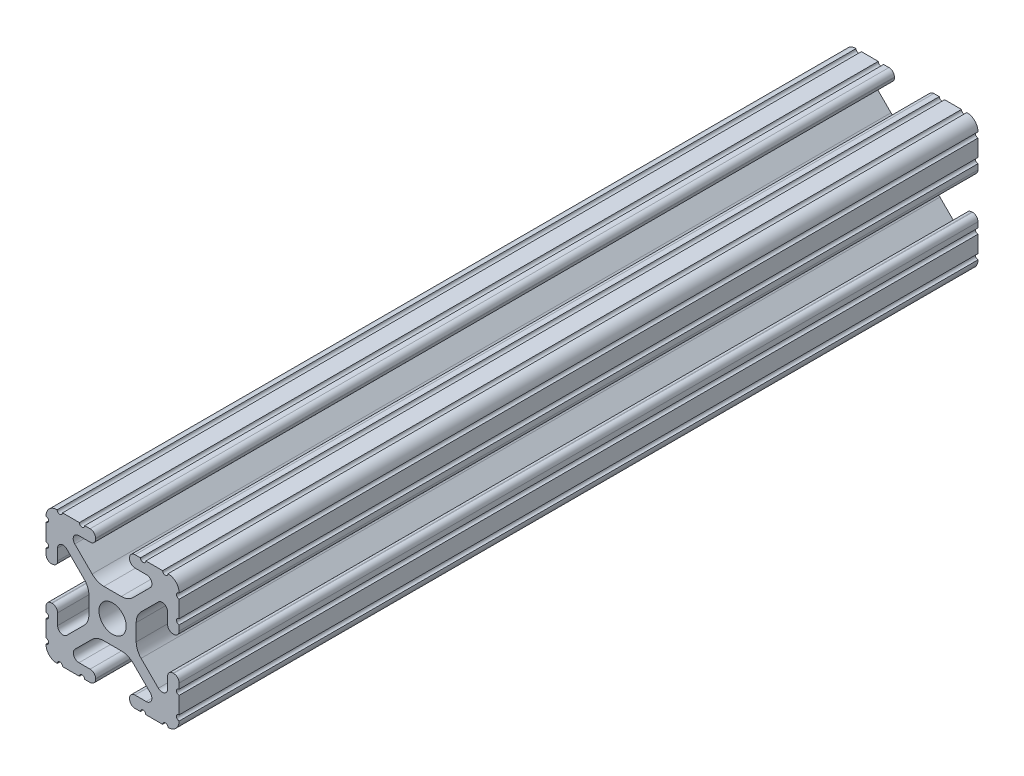
SolidWorks part; units mm, degrees
ref_plane "Front Plane" through (0, 0, 0) normal (0, 0, 1) x (1, 0, 0)
ref_plane "Top Plane" through (0, 0, 0) normal (0, 1, 0) x (1, 0, 0)
ref_plane "Right Plane" through (0, 0, 0) normal (1, 0, 0) x (0, 0, -1)
sketch "Sketch1" plane through (0, 0, 0) normal (0, 0, 1) x (1, 0, 0)
  line L88 (-7.1797, -8.6452) -> (-3.9523, -5.4237)
  line L89 (-1.7093, -4.4958) -> (1.7093, -4.4958)
  line L90 (3.9523, -5.4237) -> (7.1797, -8.6452)
  line L91 (6.4164, -10.4902) -> (4.2875, -10.4902)
  line L92 (3.2385, -11.5392) -> (3.2385, -11.651)
  line L93 (4.2875, -12.7) -> (5.3171, -12.7)
  line L94 (6.3331, -12.7) -> (9.5504, -12.7)
  line L95 (12.7, -9.5504) -> (12.7, -6.3331)
  line L96 (12.7, -5.3171) -> (12.7, -4.2875)
  line L97 (11.651, -3.2385) -> (11.5392, -3.2385)
  line L98 (10.4902, -4.2875) -> (10.4902, -6.4021)
  line L99 (8.7371, -7.1294) -> (5.441, -3.8408)
  line L100 (4.5085, -1.5932) -> (4.5085, 1.5932)
  line L101 (5.441, 3.8408) -> (8.7371, 7.1294)
  line L102 (10.4902, 6.4021) -> (10.4902, 4.2875)
  line L103 (11.5392, 3.2385) -> (11.651, 3.2385)
  line L104 (12.7, 4.2875) -> (12.7, 5.3171)
  line L105 (12.7, 6.3331) -> (12.7, 9.5504)
  line L106 (9.5504, 12.7) -> (6.3331, 12.7)
  line L107 (5.3171, 12.7) -> (4.2875, 12.7)
  line L108 (3.2385, 11.651) -> (3.2385, 11.5392)
  line L109 (4.2875, 10.4902) -> (6.4768, 10.4902)
  line L110 (7.207, 8.7244) -> (3.8983, 5.4232)
  line L111 (1.6558, 4.4958) -> (-1.6558, 4.4958)
  line L112 (-3.8983, 5.4232) -> (-7.207, 8.7244)
  line L113 (-6.4768, 10.4902) -> (-4.2875, 10.4902)
  line L114 (-3.2385, 11.5392) -> (-3.2385, 11.651)
  line L115 (-4.2875, 12.7) -> (-5.3171, 12.7)
  line L116 (-6.3331, 12.7) -> (-9.5504, 12.7)
  line L117 (-12.7, 9.5504) -> (-12.7, 6.3331)
  line L118 (-12.7, 5.3171) -> (-12.7, 4.2875)
  line L119 (-11.651, 3.2385) -> (-11.5392, 3.2385)
  line L120 (-10.4902, 4.2875) -> (-10.4902, 6.4021)
  line L121 (-8.7371, 7.1294) -> (-5.441, 3.8408)
  line L122 (-4.5085, 1.5932) -> (-4.5085, -1.5932)
  line L123 (-5.441, -3.8408) -> (-8.7371, -7.1294)
  line L124 (-10.4902, -6.4021) -> (-10.4902, -4.2875)
  line L125 (-11.5392, -3.2385) -> (-11.651, -3.2385)
  line L126 (-12.7, -4.2875) -> (-12.7, -5.3171)
  line L127 (-12.7, -6.3331) -> (-12.7, -9.5504)
  line L128 (-9.5504, -12.7) -> (-6.3331, -12.7)
  line L129 (-5.3171, -12.7) -> (-4.2875, -12.7)
  line L130 (-3.2385, -11.651) -> (-3.2385, -11.5392)
  line L131 (-4.2875, -10.4902) -> (-6.4164, -10.4902)
  circle A1 centre (0, 0) radius 2.6035
  arc A104 (-7.1797, -8.6452) -> (-6.4164, -10.4902) centre (-6.4164, -9.4098) ccw
  arc A105 (-1.7093, -4.4958) -> (-3.9523, -5.4237) centre (-1.7093, -7.6708) ccw
  arc A106 (3.9523, -5.4237) -> (1.7093, -4.4958) centre (1.7093, -7.6708) ccw
  arc A107 (6.4164, -10.4902) -> (7.1797, -8.6452) centre (6.4164, -9.4098) ccw
  arc A108 (4.2875, -10.4902) -> (3.2385, -11.5392) centre (4.2875, -11.5392) ccw
  arc A109 (3.2385, -11.651) -> (4.2875, -12.7) centre (4.2875, -11.651) ccw
  arc A110 (6.3331, -12.7) -> (5.3171, -12.7) centre (5.8251, -12.7) ccw
  arc A111 (10.5664, -12.6998) -> (9.5504, -12.7) centre (10.0584, -12.7) ccw
  arc A112 (10.5664, -12.6998) -> (12.6998, -10.5664) centre (10.5918, -10.5918) ccw
  arc A113 (12.7, -9.5504) -> (12.6998, -10.5664) centre (12.7, -10.0584) ccw
  arc A114 (12.7, -5.3171) -> (12.7, -6.3331) centre (12.7, -5.8251) ccw
  arc A115 (12.7, -4.2875) -> (11.651, -3.2385) centre (11.651, -4.2875) ccw
  arc A116 (11.5392, -3.2385) -> (10.4902, -4.2875) centre (11.5392, -4.2875) ccw
  arc A117 (8.7371, -7.1294) -> (10.4902, -6.4021) centre (9.4628, -6.4021) ccw
  arc A118 (4.5085, -1.5932) -> (5.441, -3.8408) centre (7.6835, -1.5932) ccw
  arc A119 (5.441, 3.8408) -> (4.5085, 1.5932) centre (7.6835, 1.5932) ccw
  arc A120 (10.4902, 6.4021) -> (8.7371, 7.1294) centre (9.4628, 6.4021) ccw
  arc A121 (10.4902, 4.2875) -> (11.5392, 3.2385) centre (11.5392, 4.2875) ccw
  arc A122 (11.651, 3.2385) -> (12.7, 4.2875) centre (11.651, 4.2875) ccw
  arc A123 (12.7, 6.3331) -> (12.7, 5.3171) centre (12.7, 5.8251) ccw
  arc A124 (12.6998, 10.5664) -> (12.7, 9.5504) centre (12.7, 10.0584) ccw
  arc A125 (12.6998, 10.5664) -> (10.5664, 12.6998) centre (10.5918, 10.5918) ccw
  arc A126 (9.5504, 12.7) -> (10.5664, 12.6998) centre (10.0584, 12.7) ccw
  arc A127 (5.3171, 12.7) -> (6.3331, 12.7) centre (5.8251, 12.7) ccw
  arc A128 (4.2875, 12.7) -> (3.2385, 11.651) centre (4.2875, 11.651) ccw
  arc A129 (3.2385, 11.5392) -> (4.2875, 10.4902) centre (4.2875, 11.5392) ccw
  arc A130 (7.207, 8.7244) -> (6.4768, 10.4902) centre (6.4768, 9.4563) ccw
  arc A131 (1.6558, 4.4958) -> (3.8983, 5.4232) centre (1.6558, 7.6708) ccw
  arc A132 (-3.8983, 5.4232) -> (-1.6558, 4.4958) centre (-1.6558, 7.6708) ccw
  arc A133 (-6.4768, 10.4902) -> (-7.207, 8.7244) centre (-6.4768, 9.4563) ccw
  arc A134 (-4.2875, 10.4902) -> (-3.2385, 11.5392) centre (-4.2875, 11.5392) ccw
  arc A135 (-3.2385, 11.651) -> (-4.2875, 12.7) centre (-4.2875, 11.651) ccw
  arc A136 (-6.3331, 12.7) -> (-5.3171, 12.7) centre (-5.8251, 12.7) ccw
  arc A137 (-10.5664, 12.6998) -> (-9.5504, 12.7) centre (-10.0584, 12.7) ccw
  arc A138 (-10.5664, 12.6998) -> (-12.6998, 10.5664) centre (-10.5918, 10.5918) ccw
  arc A139 (-12.7, 9.5504) -> (-12.6998, 10.5664) centre (-12.7, 10.0584) ccw
  arc A140 (-12.7, 5.3171) -> (-12.7, 6.3331) centre (-12.7, 5.8251) ccw
  arc A141 (-12.7, 4.2875) -> (-11.651, 3.2385) centre (-11.651, 4.2875) ccw
  arc A142 (-11.5392, 3.2385) -> (-10.4902, 4.2875) centre (-11.5392, 4.2875) ccw
  arc A143 (-8.7371, 7.1294) -> (-10.4902, 6.4021) centre (-9.4628, 6.4021) ccw
  arc A144 (-4.5085, 1.5932) -> (-5.441, 3.8408) centre (-7.6835, 1.5932) ccw
  arc A145 (-5.441, -3.8408) -> (-4.5085, -1.5932) centre (-7.6835, -1.5932) ccw
  arc A146 (-10.4902, -6.4021) -> (-8.7371, -7.1294) centre (-9.4628, -6.4021) ccw
  arc A147 (-10.4902, -4.2875) -> (-11.5392, -3.2385) centre (-11.5392, -4.2875) ccw
  arc A148 (-11.651, -3.2385) -> (-12.7, -4.2875) centre (-11.651, -4.2875) ccw
  arc A149 (-12.7, -6.3331) -> (-12.7, -5.3171) centre (-12.7, -5.8251) ccw
  arc A150 (-12.6998, -10.5664) -> (-12.7, -9.5504) centre (-12.7, -10.0584) ccw
  arc A151 (-12.6998, -10.5664) -> (-10.5664, -12.6998) centre (-10.5918, -10.5918) ccw
  arc A152 (-9.5504, -12.7) -> (-10.5664, -12.6998) centre (-10.0584, -12.7) ccw
  arc A153 (-5.3171, -12.7) -> (-6.3331, -12.7) centre (-5.8251, -12.7) ccw
  arc A154 (-4.2875, -12.7) -> (-3.2385, -11.651) centre (-4.2875, -11.651) ccw
  arc A155 (-3.2385, -11.5392) -> (-4.2875, -10.4902) centre (-4.2875, -11.5392) ccw
extrude "Boss-Extrude1" add sketch "Sketch1" along normal mid plane 304.8
sketch "Sketch2" plane through (0, 0, 0) normal (0, 1, 0) x (1, 0, 0)
  line L1 (12.6998, 152.4) -> (-59.9921, 152.4)
  line L3 (12.6998, 0) -> (-59.9921, 0)
  line L4 (-59.9921, 152.4) -> (-59.9921, 0)
  line L5 (12.6998, 0) -> (35.1875, 0)
  line L7 (12.6998, 152.4) -> (35.1875, 152.4)
  line L8 (35.1875, 0) -> (35.1875, 152.4)
  dimension "D1" = 152.4
extrude "Cut-Extrude1" cut sketch "Sketch2" against normal blind 151.384 and the other way blind 126.238
